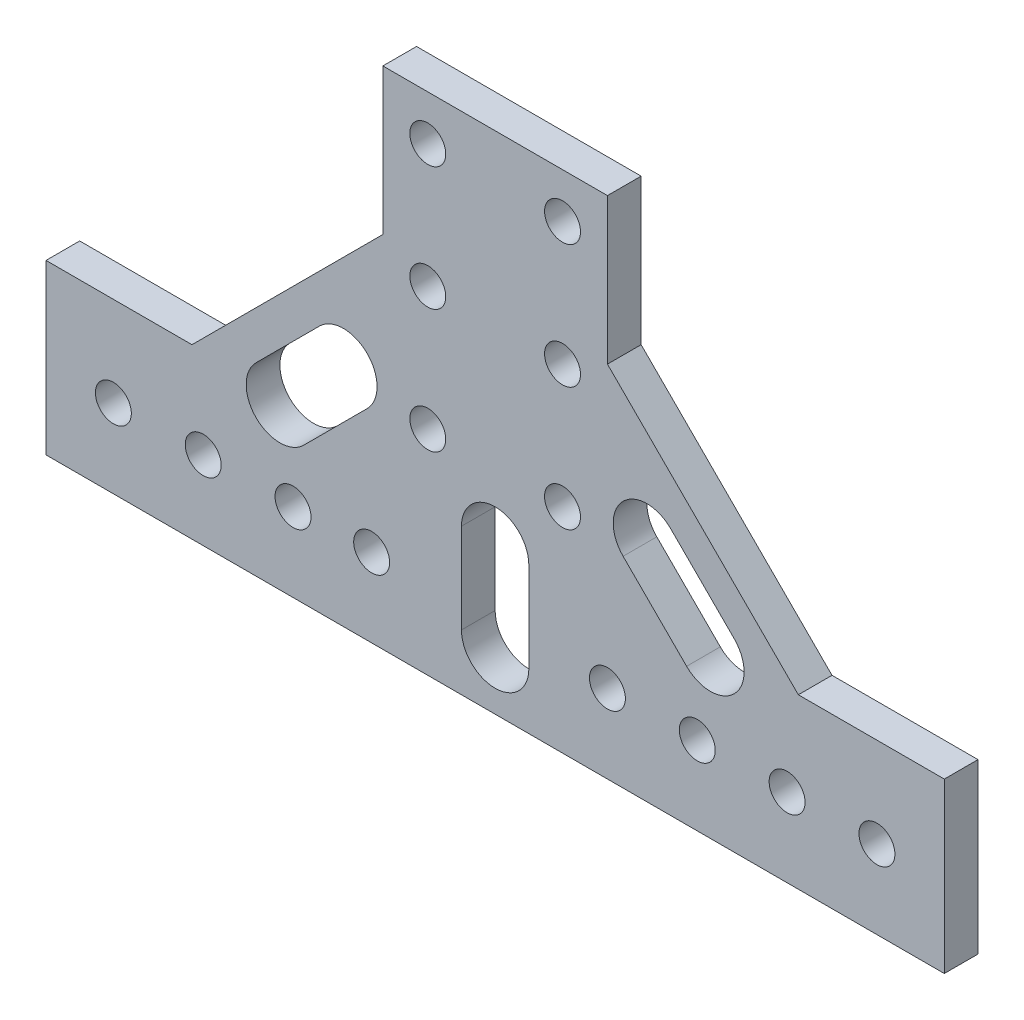
SolidWorks part; units mm, degrees
material "Thornel VCB-20 碳布"
ref_plane "前视基准面" through (0, 0, 0) normal (0, 0, 1) x (1, 0, 0)
ref_plane "上视基准面" through (0, 0, 0) normal (0, 1, 0) x (1, 0, 0)
ref_plane "右视基准面" through (0, 0, 0) normal (1, 0, 0) x (0, 0, -1)
other "Configuration Table"
sketch "草图1" plane through (0, 0, 0) normal (0, 0, 1) x (1, 0, 0)
  line L0 (0, 0) -> (0, 15)
  line L1 (0, 15) -> (13, 15)
  line L2 (13, 15) -> (30, 32)
  line L3 (30, 32) -> (30, 45)
  line L4 (30, 45) -> (50, 45)
  line L5 (50, 45) -> (50, 32)
  line L6 (50, 32) -> (67, 15)
  line L7 (67, 15) -> (80, 15)
  line L8 (80, 15) -> (80, 0)
  line L9 (80, 0) -> (0, 0)
  line L10 (50, 32) -> (30, 32) construction
  dimension "D1" = 20
  dimension "D2" = 15
  dimension "D3" = 45
  dimension "D4" = 45
  dimension "D5" = 17
  dimension "D6" = 30
  dimension "D7" = 30
extrude "凸台-拉伸1" add sketch "草图1" along normal blind 3
sketch "草图3" plane through (0, 0, 0) normal (0, 0, -1) x (-1, 0, 0)
  line L0 (-30, 45) -> (-30, 32) construction
  line L1 (-46, 41) -> (-34, 41) construction
  line L2 (-46, 41) -> (-46, 19) construction
  line L3 (-46, 19) -> (-34, 19) construction
  line L4 (-34, 41) -> (-34, 19) construction
  line L5 (-50, 45) -> (-30, 45) construction
  line L6 (-13, 15) -> (0, 15) construction
  line L7 (-74, 7) -> (-6, 7) construction
  line L8 (-80, 0) -> (-80, 15) construction
  line L9 (0, 15) -> (0, 0) construction
  line L10 (0, 0) -> (-80, 0) construction
  line L11 (-59.1716, 14.3431) -> (-53.5147, 20) construction
  line L12 (-61.2929, 16.4645) -> (-55.636, 22.1213)
  line L13 (-57.0503, 12.2218) -> (-51.3934, 17.8787)
  line L14 (-20.8284, 14.3431) -> (-26.4853, 20) construction
  line L15 (-22.9497, 12.2218) -> (-28.6066, 17.8787)
  line L16 (-18.7071, 16.4645) -> (-24.364, 22.1213)
  line L18 (-53.5147, 20) -> (-26.4853, 20) construction
  line L19 (-59.1716, 14.3431) -> (-20.8284, 14.3431) construction
  line L20 (-30, 32) -> (-13, 15) construction
  line L21 (-67, 15) -> (-50, 32) construction
  line L22 (-40, 5) -> (-40, 13) construction
  line L23 (-43, 5) -> (-43, 13)
  line L24 (-37, 5) -> (-37, 13)
  line L25 (-40, 0) -> (-40, 45) construction
  circle A0 centre (-46, 41) radius 1.6
  circle A1 centre (-34, 41) radius 1.6
  circle A2 centre (-46, 19) radius 1.6
  circle A3 centre (-34, 19) radius 1.6
  circle A4 centre (-34, 30) radius 1.6
  circle A5 centre (-46, 30) radius 1.6
  circle A6 centre (-74, 7) radius 1.6
  circle A7 centre (-66, 7) radius 1.6
  circle A8 centre (-58, 7) radius 1.6
  circle A9 centre (-50, 7) radius 1.6
  circle A10 centre (-6, 7) radius 1.6
  circle A11 centre (-14, 7) radius 1.6
  circle A12 centre (-22, 7) radius 1.6
  circle A13 centre (-29, 7) radius 1.6
  arc A14 (-61.2929, 16.4645) -> (-57.0503, 12.2218) centre (-59.1716, 14.3431) ccw
  arc A15 (-51.3934, 17.8787) -> (-55.636, 22.1213) centre (-53.5147, 20) ccw
  arc A16 (-22.9497, 12.2218) -> (-18.7071, 16.4645) centre (-20.8284, 14.3431) ccw
  arc A17 (-24.364, 22.1213) -> (-28.6066, 17.8787) centre (-26.4853, 20) ccw
  arc A18 (-43, 5) -> (-37, 5) centre (-40, 5) ccw
  arc A19 (-37, 13) -> (-43, 13) centre (-40, 13) ccw
  point P42 (-56.3431, 17.1716)
  point P47 (-23.6569, 17.1716)
  point P64 (-40, 9)
  point P69 (-40, 15.7824)
  dimension "D5" = 3.2
  dimension "D9" = 3.2
  dimension "D18" = 3
  dimension "D20" = 6
  dimension "D22" = 3
  dimension "D1" = 12
  dimension "D2" = 4
  dimension "D3" = 4
  dimension "D4" = 4
  dimension "D6" = 6
  dimension "D7" = 6
  dimension "D8" = 7
  dimension "D10" = 8
  dimension "D11" = 8
  dimension "D12" = 8
  dimension "D13" = 8
  dimension "D14" = 8
  dimension "D15" = 7
  dimension "D16" = 135
  dimension "D17" = 8
  dimension "D19" = 20
  dimension "D21" = 6
  dimension "D23" = 8
  dimension "D24" = 5
extrude "切除-拉伸1" cut sketch "草图3" against normal through all
